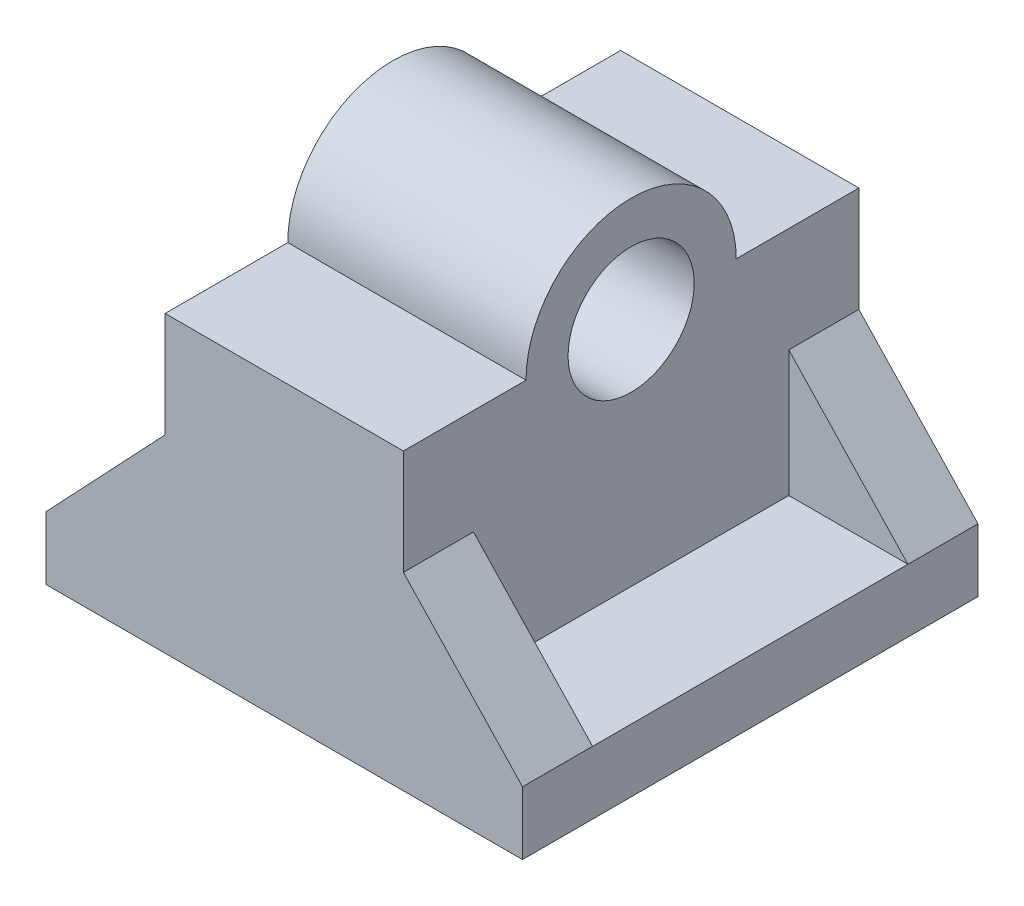
SolidWorks part; units mm, degrees
ref_plane "Front Plane" through (0, 0, 0) normal (0, 0, 1) x (1, 0, 0)
ref_plane "Top Plane" through (0, 0, 0) normal (0, 1, 0) x (1, 0, 0)
ref_plane "Right Plane" through (0, 0, 0) normal (1, 0, 0) x (0, 0, -1)
sketch "Sketch1" plane through (0, 0, 0) normal (0, 0, 1) x (1, 0, 0)
  line L0 (-34, 0) -> (-34, 9)
  line L1 (-34, 9) -> (-17, 27)
  line L2 (-17, 27) -> (-17, 42)
  line L3 (-17, 42) -> (17, 42)
  line L4 (-34, 0) -> (34, 0)
  line L5 (0, -30.9729) -> (0, 97.5578) construction
  line L6 (34, 0) -> (34, 9)
  line L7 (17, 27) -> (17, 42)
  line L8 (34, 9) -> (17, 27)
  point P9 (0, 0)
  point P13 (0, 0)
  dimension "D1" = 68
  dimension "D2" = 34
  dimension "D3" = 42
  dimension "D4" = 15
  dimension "D5" = 18
extrude "Boss-Extrude1" add sketch "Sketch1" against normal blind 65
sketch "Sketch2" plane through (-17, 0, 0) normal (-1, 0, 0) x (0, 0, 1)
  line L0 (-65, 42) -> (0, 42) construction
  circle A0 centre (-32.5, 42) radius 15
extrude "Boss-Extrude2" add sketch "Sketch2" against normal blind 34
sketch "Sketch3" plane through (-17, 0, 0) normal (-1, 0, 0) x (0, 0, 1)
  circle A0 centre (-32.5, 42) radius 9
  dimension "D1" = 18
extrude "Cut-Extrude1" cut sketch "Sketch3" against normal blind 34
ref_plane "Plane1" through (-34, 0, 0) normal (1, 0, 0) x (0, 0, -1)
sketch "Sketch4" plane through (-34, 0, 0) normal (1, 0, 0) x (0, 0, -1)
  line L0 (10, 9) -> (10, 27)
  line L1 (65, 9) -> (0, 9) construction
  line L2 (65, 27) -> (0, 27) construction
  line L3 (10, 27) -> (55, 27)
  line L4 (55, 27) -> (55, 9)
  line L5 (55, 9) -> (10, 9)
  dimension "D1" = 10
  dimension "D2" = 10
extrude "Cut-Extrude2" cut sketch "Sketch4" along normal blind 17
mirror "Mirror1" about plane through (0, 0, 0) normal (1, 0, 0) of "Cut-Extrude2"
